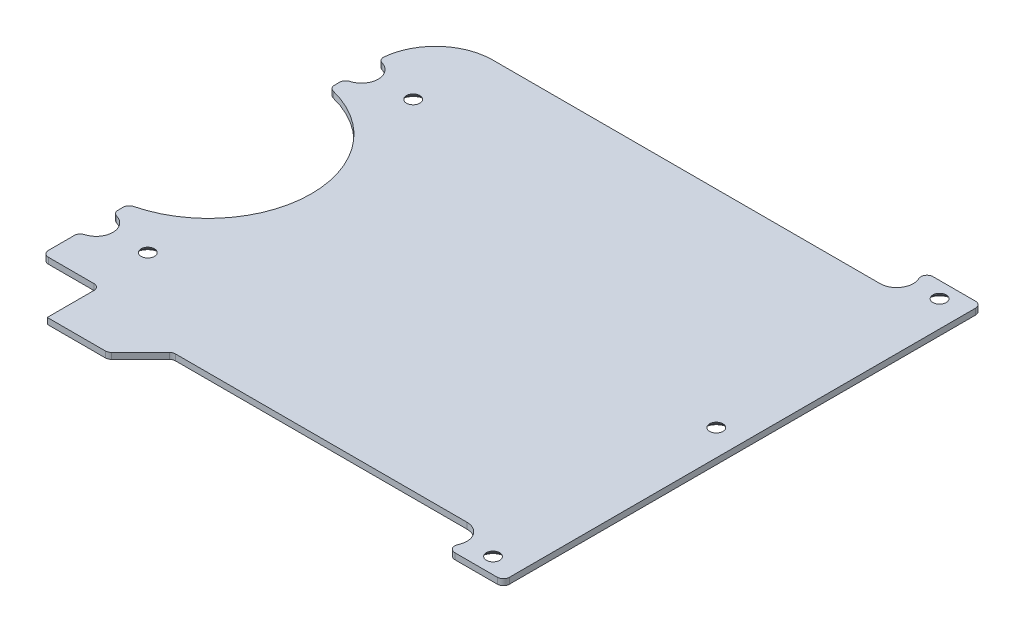
SolidWorks part; units mm, degrees
ref_plane "Front Plane" through (0, 0, 0) normal (0, 0, 1) x (1, 0, 0)
ref_plane "Top Plane" through (0, 0, 0) normal (0, 1, 0) x (1, 0, 0)
ref_plane "Right Plane" through (0, 0, 0) normal (1, 0, 0) x (0, 0, -1)
sketch "Sketch1" plane through (0, 0, 0) normal (0, 1, 0) x (1, 0, 0)
  line L0 (0, 30.3854) -> (0, -26.0557) construction
  line L1 (-19.0199, 0) -> (15.6179, 0) construction
  line L2 (-73.452, 57.1764) -> (-73.452, -39.7909) construction
  line L3 (0, 34.13) -> (-63.992, 34.13)
  line L4 (0, -34.13) -> (-48.582, -34.13)
  line L5 (-73.452, 19.17) -> (-73.452, 16.6626)
  line L6 (-48.582, -34.13) -> (-53.952, -39.5)
  line L7 (-63.952, -34.13) -> (-63.952, -39.5)
  line L8 (-73.452, -19.17) -> (-73.452, -16.6626)
  line L9 (11.4, 39.5) -> (11.4, -39.5)
  line L10 (11.4, 39.5) -> (0.8355, 39.5)
  line L11 (11.4, -39.5) -> (0.8355, -39.5)
  line L12 (-48.582, -34.13) -> (-73.452, -34.13) construction
  line L13 (-63.952, -39.5) -> (-53.952, -39.5)
  line L14 (-73.452, -24.67) -> (-73.452, -30.8)
  line L15 (-63.952, 0) -> (-63.952, -34.13) construction
  line L16 (-73.452, -30.8) -> (-63.952, -30.8)
  line L17 (-63.952, -30.8) -> (-63.952, -34.13)
  line L18 (2.75, 36.88) -> (2.75, -36.88) construction
  line L19 (2.75, 36.88) -> (11.4, 36.88) construction
  line L20 (-73.452, 21.92) -> (11.4, 21.92) construction
  line L21 (7.075, 36.88) -> (7.075, -36.88) construction
  circle A0 centre (0, 36.88) radius 2.5
  circle A1 centre (0, -36.88) radius 2.5
  circle A2 centre (-73.452, 21.92) radius 2.5
  circle A3 centre (-73.452, -21.92) radius 2.5
  circle A4 centre (-76.822, 0) radius 16
  circle A5 centre (-73.452, 21.92) radius 2.75
  circle A6 centre (-76.822, 0) radius 17
  circle A7 centre (-73.452, -21.92) radius 2.75
  circle A8 centre (0, 36.88) radius 2.75
  circle A9 centre (0, -36.88) radius 2.75
  arc A10 (-73.452, 24.67) -> (-63.992, 34.13) centre (-63.992, 24.67) cw
  circle A11 centre (7.075, 36.88) radius 1
  circle A12 centre (7.075, -36.88) radius 1
  circle A13 centre (-64.925, 21.92) radius 1
  circle A14 centre (-64.925, -21.92) radius 1
  circle A15 centre (7.075, 0) radius 1
  point P39 (11.4, 0)
  dimension "D2" = 5
  dimension "D3" = 43.84
  dimension "D5" = 32
  dimension "D16" = 2
  dimension "D1" = 73.76
  dimension "D4" = 74.96
  dimension "D6" = 3.37
  dimension "D12" = 79
  dimension "D13" = 11.4
  dimension "D9" = 10
  dimension "D10" = 45
  dimension "D11" = 5.37
  dimension "D14" = 8.7
  dimension "D15" = 9.5
  dimension "D17" = 72
  dimension "D7" = 0.25
  dimension "D8" = 1
extrude "Base shape" add sketch "Sketch1" along normal blind 1
fillet "Fillets" radius 1 14 edges at (-48.582, 0.5, 34.13) (-53.952, 0.5, 39.5) (-73.452, 0.5, -24.67) (-73.452, 0.5, -19.17) (-73.452, 0.5, -16.6626) (-73.452, 0.5, 24.67) (-73.452, 0.5, 19.17) (-73.452, 0.5, 16.6626) (-73.452, 0.5, 30.8) (-63.952, 0.5, 30.8) (0.8355, 0.5, -39.5) (0.8355, 0.5, 39.5) (11.4, 0.5, -39.5) (11.4, 0.5, 39.5)
hole_wizard "M2 countersunks" positions "Sketch2" profile "Sketch3" countersink size "M2" standard "ANSI Metric" end condition through all
sketch "Sketch2" plane through (0, 0, 0) normal (0, -1, 0) x (-1, 0, 0)
  point P0 (-7.075, 36.88)
  point P3 (-7.075, -36.88)
  point P6 (64.925, 21.92)
  point P9 (64.925, -21.92)
  point P13 (-7.075, 0)
sketch "Sketch3" plane through (7.075, 0, -36.88) normal (1, 0, 0) x (0, 0, -1)
  line L0 (0, 0) -> (0, 1)
  line L1 (0, 1) -> (1, 1)
  line L2 (1, 1) -> (1, 1.1)
  line L3 (1, 1.1) -> (2, 0.1)
  line L4 (2, 0.1) -> (2, 0)
  line L6 (2, 0) -> (0, 0)
  line L7 (-1, 1.1) -> (-2, 0.1) construction
  line L11 (0, -6.35) -> (0, 107.95) construction
  dimension "Thru Hole Dia." = 2
  dimension "Thru Hole Depth" = 1
  dimension "C'Sink Dia." = 4
  dimension "C'Sink Angle" = 90
  dimension "Head Clearance" = 0.1
